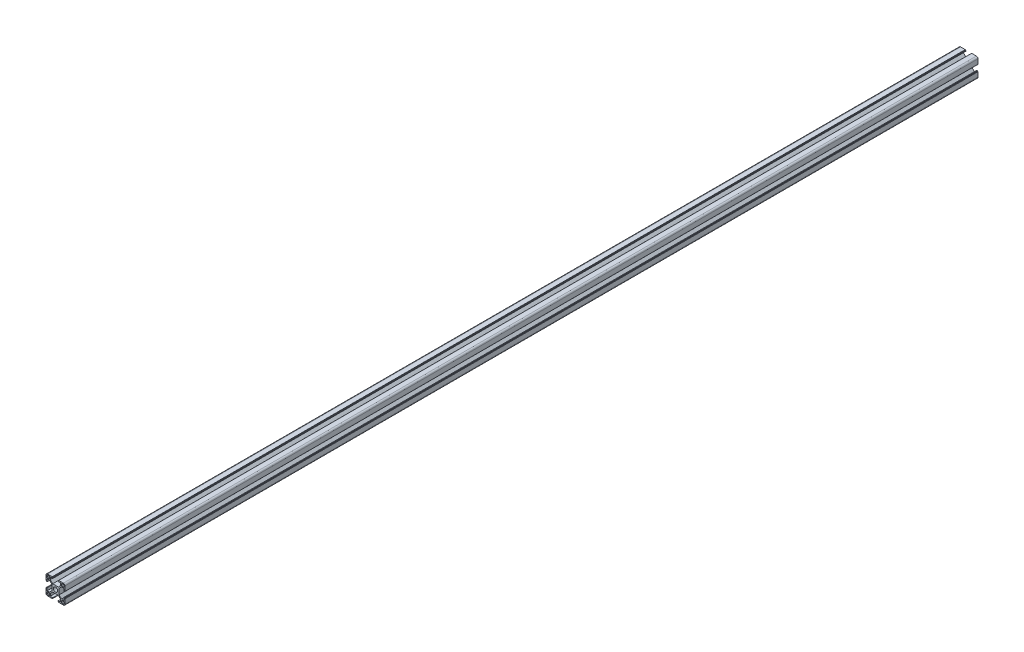
SolidWorks part; units mm, degrees
material "6061-T6 (SS)"
ref_plane "前视基准面" through (0, 0, 0) normal (0, 0, 1) x (1, 0, 0)
ref_plane "上视基准面" through (0, 0, 0) normal (0, 1, 0) x (1, 0, 0)
ref_plane "右视基准面" through (0, 0, 0) normal (1, 0, 0) x (0, 0, -1)
sketch "Sketch1" plane through (0, 0, 0) normal (0, 0, 1) x (1, 0, 0)
  line L0 (-5.1, 15) -> (-5.1, 14.2)
  line L1 (-12.5, -15) -> (12.5, -15)
  line L2 (-15, -12.5) -> (-15, 12.5)
  line L3 (-12.5, 15) -> (12.5, 15)
  line L4 (15, -12.5) -> (15, 12.5)
  line L5 (-15, -15) -> (15, 15) construction
  line L6 (-15, 15) -> (15, -15) construction
  line L7 (-5.1, 14.2) -> (-4.1, 14.2)
  line L8 (-4.1, 14.2) -> (-4.1, 13.2)
  line L9 (-4.1, 13.2) -> (-8.25, 13.2)
  line L10 (-8.25, 13.2) -> (-8.25, 9.5228)
  line L11 (-8.25, 9.5228) -> (-4.4272, 5.7)
  line L12 (-4.4272, 5.7) -> (4.4272, 5.7)
  line L13 (-5.1, 15) -> (5.1, 15)
  line L14 (0, 15) -> (0, 5.7) construction
  line L15 (8.25, 9.5228) -> (4.4272, 5.7)
  line L16 (8.25, 13.2) -> (8.25, 9.5228)
  line L17 (4.1, 13.2) -> (8.25, 13.2)
  line L18 (4.1, 14.2) -> (4.1, 13.2)
  line L19 (5.1, 14.2) -> (4.1, 14.2)
  line L20 (5.1, 15) -> (5.1, 14.2)
  line L21 (15, 5.1) -> (14.2, 5.1)
  line L22 (14.2, 5.1) -> (14.2, 4.1)
  line L23 (14.2, 4.1) -> (13.2, 4.1)
  line L24 (13.2, 4.1) -> (13.2, 8.25)
  line L25 (13.2, 8.25) -> (9.5228, 8.25)
  line L26 (9.5228, 8.25) -> (5.7, 4.4272)
  line L27 (5.7, 4.4272) -> (5.7, -4.4272)
  line L28 (15, 5.1) -> (15, -5.1)
  line L29 (9.5228, -8.25) -> (5.7, -4.4272)
  line L30 (13.2, -8.25) -> (9.5228, -8.25)
  line L31 (13.2, -4.1) -> (13.2, -8.25)
  line L32 (14.2, -4.1) -> (13.2, -4.1)
  line L33 (14.2, -5.1) -> (14.2, -4.1)
  line L34 (15, -5.1) -> (14.2, -5.1)
  line L35 (15, 0) -> (5.7, 0) construction
  line L36 (5.1, -15) -> (5.1, -14.2)
  line L37 (5.1, -14.2) -> (4.1, -14.2)
  line L38 (4.1, -14.2) -> (4.1, -13.2)
  line L39 (4.1, -13.2) -> (8.25, -13.2)
  line L40 (8.25, -13.2) -> (8.25, -9.5228)
  line L41 (8.25, -9.5228) -> (4.4272, -5.7)
  line L42 (4.4272, -5.7) -> (-4.4272, -5.7)
  line L43 (5.1, -15) -> (-5.1, -15)
  line L44 (-8.25, -9.5228) -> (-4.4272, -5.7)
  line L45 (-8.25, -13.2) -> (-8.25, -9.5228)
  line L46 (-4.1, -13.2) -> (-8.25, -13.2)
  line L47 (-4.1, -14.2) -> (-4.1, -13.2)
  line L48 (-5.1, -14.2) -> (-4.1, -14.2)
  line L49 (-5.1, -15) -> (-5.1, -14.2)
  line L50 (0, -15) -> (0, -5.7) construction
  line L51 (-15, -5.1) -> (-14.2, -5.1)
  line L52 (-14.2, -5.1) -> (-14.2, -4.1)
  line L53 (-14.2, -4.1) -> (-13.2, -4.1)
  line L54 (-13.2, -4.1) -> (-13.2, -8.25)
  line L55 (-13.2, -8.25) -> (-9.5228, -8.25)
  line L56 (-9.5228, -8.25) -> (-5.7, -4.4272)
  line L57 (-5.7, -4.4272) -> (-5.7, 4.4272)
  line L58 (-15, -5.1) -> (-15, 5.1)
  line L59 (-9.5228, 8.25) -> (-5.7, 4.4272)
  line L60 (-13.2, 8.25) -> (-9.5228, 8.25)
  line L61 (-13.2, 4.1) -> (-13.2, 8.25)
  line L62 (-14.2, 4.1) -> (-13.2, 4.1)
  line L63 (-14.2, 5.1) -> (-14.2, 4.1)
  line L64 (-15, 5.1) -> (-14.2, 5.1)
  line L65 (-15, 0) -> (-5.7, 0) construction
  line L66 (0, 0) -> (0, 5.7) construction
  circle A0 centre (0, 0) radius 3.4
  arc A1 (-12.5, -15) -> (-15, -12.5) centre (-12.5, -12.5) cw
  arc A2 (12.5, -15) -> (15, -12.5) centre (12.5, -12.5) ccw
  arc A3 (12.5, 15) -> (15, 12.5) centre (12.5, 12.5) cw
  arc A4 (-15, 12.5) -> (-12.5, 15) centre (-12.5, 12.5) cw
  point P0 (0, 0)
  dimension "D3" = 6.8
  dimension "D12" = 2.5
  dimension "D1" = 30
  dimension "D2" = 30
  dimension "D4" = 16.5
  dimension "D5" = 8.2
  dimension "D6" = 10.2
  dimension "D7" = 7.5
  dimension "D9" = 1.8
  dimension "D10" = 1.8
  dimension "D11" = 0.8
  dimension "D8" = 4
extrude "Extrude1" add sketch "Sketch1" along normal blind 1441 contours A4 L2 L64 L63 L62 L61 L60 L59 L57 L56 L55 L54 L53 L52 L51 A1 L1 L49 L48 L47 L46 L45 L44 L42 L41 L40 L39 L38 L37 L36 A2 L4 L34 L33 L32 L31 L30 L29 L27 L26 L25 L24 L23 L22 L21 A3 L3 L20
sketch "Sketch2" plane through (0, 0, 1441) normal (0, 0, 1) x (1, 0, 0)
  line L0 (13.7, 12.7) -> (13.7, 10.55)
  line L1 (-12.7, 13.7) -> (-10.55, 13.7)
  line L2 (-13.7, 12.7) -> (-13.7, 10.55)
  line L3 (-12.7, 9.55) -> (-10.55, 9.55)
  line L4 (-9.55, 12.7) -> (-9.55, 10.55)
  line L5 (-13.7, 13.7) -> (-9.55, 9.55) construction
  line L6 (-13.7, 9.55) -> (-9.55, 13.7) construction
  line L7 (12.7, 13.7) -> (10.55, 13.7)
  line L8 (9.55, 12.7) -> (9.55, 10.55)
  line L9 (12.7, 9.55) -> (10.55, 9.55)
  line L10 (12.7, -13.7) -> (10.55, -13.7)
  line L11 (13.7, -12.7) -> (13.7, -10.55)
  line L12 (12.7, -9.55) -> (10.55, -9.55)
  line L13 (9.55, -12.7) -> (9.55, -10.55)
  line L14 (-13.7, -12.7) -> (-13.7, -10.55)
  line L15 (-12.7, -13.7) -> (-10.55, -13.7)
  line L16 (-9.55, -12.7) -> (-9.55, -10.55)
  line L17 (-12.7, -9.55) -> (-10.55, -9.55)
  line L18 (0, 0) -> (-9.55, 9.55) construction
  line L19 (-12.5, 15) -> (-5.1, 15) construction
  line L20 (-15, 5.1) -> (-15, 12.5) construction
  line L21 (-13.2, 8.25) -> (-9.5228, 8.25) construction
  line L22 (-8.25, 13.2) -> (-8.25, 9.5228) construction
  arc A0 (-13.7, -12.7) -> (-12.7, -13.7) centre (-12.7, -12.7) ccw
  arc A1 (-10.55, -13.7) -> (-9.55, -12.7) centre (-10.55, -12.7) ccw
  arc A2 (-9.55, -10.55) -> (-10.55, -9.55) centre (-10.55, -10.55) ccw
  arc A3 (-13.7, -10.55) -> (-12.7, -9.55) centre (-12.7, -10.55) cw
  arc A4 (13.7, -10.55) -> (12.7, -9.55) centre (12.7, -10.55) ccw
  arc A5 (12.7, -13.7) -> (13.7, -12.7) centre (12.7, -12.7) ccw
  arc A6 (10.55, -13.7) -> (9.55, -12.7) centre (10.55, -12.7) cw
  arc A7 (10.55, -9.55) -> (9.55, -10.55) centre (10.55, -10.55) ccw
  arc A8 (13.7, 12.7) -> (12.7, 13.7) centre (12.7, 12.7) ccw
  arc A9 (13.7, 10.55) -> (12.7, 9.55) centre (12.7, 10.55) cw
  arc A10 (9.55, 10.55) -> (10.55, 9.55) centre (10.55, 10.55) ccw
  arc A11 (10.55, 13.7) -> (9.55, 12.7) centre (10.55, 12.7) ccw
  arc A12 (-10.55, 13.7) -> (-9.55, 12.7) centre (-10.55, 12.7) cw
  arc A13 (-10.55, 9.55) -> (-9.55, 10.55) centre (-10.55, 10.55) ccw
  arc A14 (-13.7, 10.55) -> (-12.7, 9.55) centre (-12.7, 10.55) ccw
  arc A15 (-12.7, 13.7) -> (-13.7, 12.7) centre (-12.7, 12.7) ccw
  point P0 (-11.625, 11.625)
  dimension "D2" = 1
  dimension "D3" = 1.3
  dimension "D4" = 1.3
  dimension "D5" = 1.3
  dimension "D6" = 1.3
  dimension "D1" = 4
extrude "Extrude2" cut sketch "Sketch2" against normal through all
